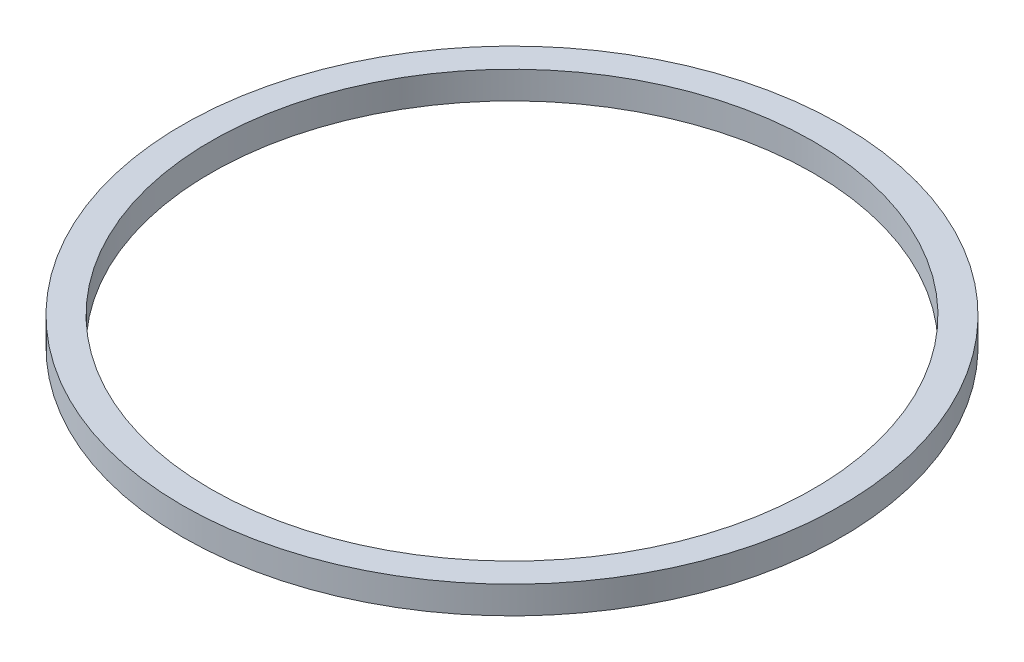
SolidWorks part; units mm, degrees
ref_plane "Front Plane" through (0, 0, 0) normal (0, 0, 1) x (1, 0, 0)
ref_plane "Top Plane" through (0, 0, 0) normal (0, 1, 0) x (1, 0, 0)
ref_plane "Right Plane" through (0, 0, 0) normal (1, 0, 0) x (0, 0, -1)
sketch "Sketch1" plane through (0, 0, 0) normal (0, 1, 0) x (1, 0, 0)
  circle A0 centre (0, 0) radius 12
  circle A1 centre (0, 0) radius 10.968
  dimension "D1" = 24
  dimension "D2" = 21.936
extrude "Boss-Extrude1" add sketch "Sketch1" along normal blind 1
